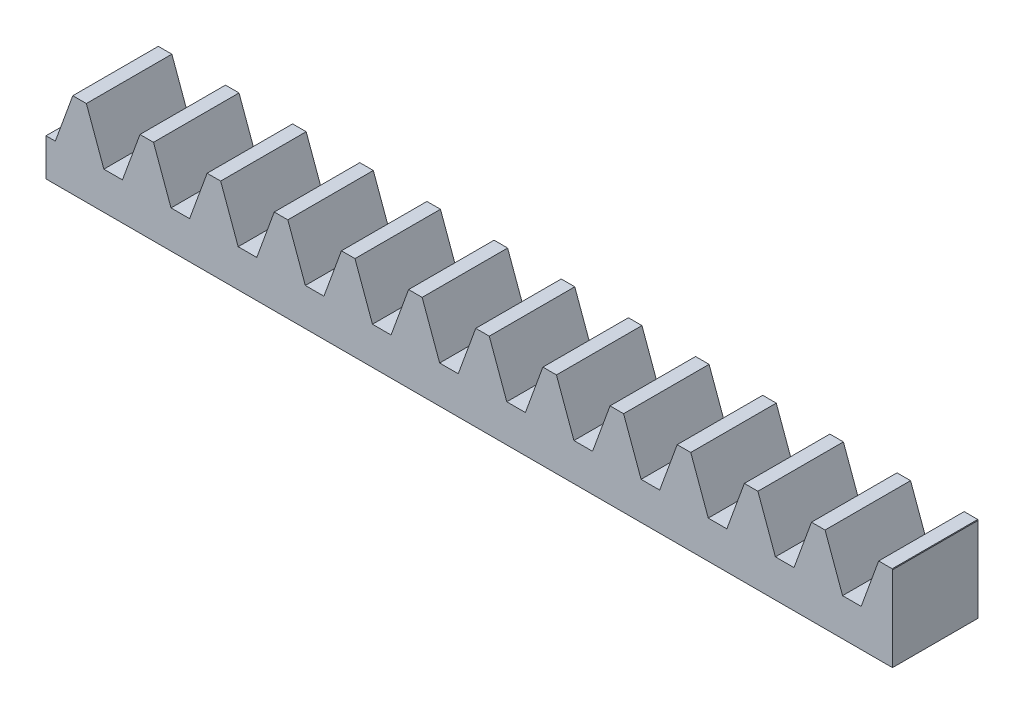
SolidWorks part; units mm, degrees
extrude "Blank" add sketch "BlankSke" against normal blind 10
sketch "BlankSke" plane through (0, 0, 0) normal (0, 0, 1) x (1, 0, 0)
  line L1 (0, 0) -> (99, 0)
  line L2 (0, 0) -> (0, 10)
  line L3 (0, 10) -> (99, 10)
  line L4 (99, 0) -> (99, 10)
  dimension "Length" = 99
  dimension "Blank_height" = 10
ref_plane "Plane1" through (0, 0, 0) normal (0, 0, 1) x (1, 0, 0)
ref_plane "Plane2" through (0, 0, 0) normal (0, 1, 0) x (1, 0, 0)
ref_plane "Plane3" through (0, 0, 0) normal (1, 0, 0) x (0, 0, -1)
sketch "HoldingSke" plane through (0, 0, 0) normal (0, 1, 0) x (1, 0, 0)
  line L0 (0, 0) -> (0.0557, 0.3961)
  line L1 (-15, 0) -> (100, 0) construction
  line L2 (0, 0) -> (-2.1039, 2.3779)
  line L3 (0, 0) -> (-11.863, 4.5341)
  line L4 (0, 0) -> (8.3795, 2.0892)
  line L5 (0, 0) -> (-23.7986, -8.8762)
  line L6 (0, 0) -> (-10.5278, -7.1032)
  line L9 (-71.009, 38.7566) -> (22.0206, 72.6166)
  line L10 (-76.2, 4.8779) -> (-68.7, 4.8779)
  line L11 (0, 0) -> (-10, 0)
  line L12 (-76.2, 101.6) -> (-76.113, 101.6)
  line L13 (24.9733, 27.94) -> (52.9518, 28.4284)
  line L14 (24.9733, 27.94) -> (24.9743, 27.94)
  line L15 (24.9733, 27.94) -> (100.4006, 29.5858)
  circle A0 centre (0, 0) radius 19.05
  circle A1 centre (0, 0) radius 3.75
  circle A2 centre (0, 0) radius 12.7
  dimension "MPH" = 7.5
  dimension "Diameter" = 38.1
  dimension "Num_teeth" = 14
  dimension "Pitch" = 0.4
  dimension "Show_teeth" = 998
  dimension "Thickness" = 12.7
  dimension "Ap" = 20
  dimension "Pitch_height" = 7.5
  dimension "Width" = 10
  dimension "Backlash" = 0.087
  dimension "Addendum_fac" = 1
  dimension "Dedendum_fac" = 1.25
  dimension "Clearance_fac" = 0.25
  dimension "Dedendum_add" = 0.001
  dimension "Length" = 99
  dimension "Module" = 2.5
sketch "TooCutSkeIll" plane through (0, 0, 0) normal (0, 0, 1) x (1, 0, 0)
  line L0 (-3.1105, 9.9342) -> (-1.237, 4.7869)
  line L1 (-0.6488, 4.375) -> (0.6488, 4.375)
  line L2 (1.237, 4.7869) -> (3.1105, 9.9342)
  line L3 (99, 10) -> (0, 10) construction
  line L4 (0, 0) -> (0, 64.897) construction
  line L5 (-13.208, 7.5) -> (12.954, 7.5) construction
  line L6 (0, 0) -> (99, 0) construction
  line L7 (2.2245, 7.5) -> (2.2245, 48.7463) construction
  line L8 (-2.2245, 7.5) -> (-2.2245, 48.7463) construction
  line L9 (3.2044, 10) -> (3.2044, 10.0254)
  line L10 (-3.2044, 10) -> (-3.2044, 10.0254)
  line L11 (-3.2044, 10.0254) -> (3.2044, 10.0254)
  arc A0 (0.6488, 4.375) -> (1.237, 4.7869) centre (0.6488, 5.001) ccw
  arc A1 (-1.237, 4.7869) -> (-0.6488, 4.375) centre (-0.6488, 5.001) ccw
  arc A2 (3.2044, 10) -> (3.1105, 9.9342) centre (3.2044, 9.9) ccw
  arc A3 (-3.1105, 9.9342) -> (-3.2044, 10) centre (-3.2044, 9.9) ccw
  dimension "Pitch_height" = 7.5
  dimension "Addendum_plus" = 2.5254
  dimension "Pressure_angle" = 20
  dimension "Gap_width" = 4.449
  dimension "Dedendum" = 3.125
extrude "ToothCutIll" [suppressed] cut sketch "TooCutSkeIll" against normal through all
sketch "TooCutSkeSim" plane through (0, 0, 0) normal (0, 0, 1) x (1, 0, 0)
  line L0 (1.0871, 4.375) -> (-1.0871, 4.375)
  line L1 (3.1437, 10.0254) -> (1.0871, 4.375)
  line L2 (0, 17.4625) -> (0, 53.467) construction
  line L3 (3.1437, 10.0254) -> (-3.1437, 10.0254)
  line L6 (-3.1437, 10.0254) -> (-1.0871, 4.375)
  line L9 (-2.2245, 7.5) -> (2.2245, 7.5) construction
  line L10 (0, 0) -> (99, 0) construction
  line L11 (2.2245, 7.5) -> (2.2245, 53.467) construction
  line L12 (-2.2245, 7.5) -> (-2.2245, 53.467) construction
  dimension "Pitch_height" = 7.5
  dimension "Addendum_plus" = 2.5254
  dimension "Pressure_angle" = 20
  dimension "Gap_width" = 4.449
  dimension "Dedendum" = 3.125
extrude "ToothCutSim" cut sketch "TooCutSkeSim" against normal through all
pattern_linear "TeethCuts" count 13 spacing 7.854 along (1, 0, 0) of "ToothCutIll", "ToothCutSim"
equation "' \"Module@HoldingSke\" = 6.35"
equation "' \"Num_teeth@HoldingSke\" = 12"
equation "' \"Ap@HoldingSke\" =  20"
equation "' \"Ap@HoldingSke\" = 20"
equation "' \"Width@HoldingSke\" = 0.25 * 25.4"
equation "' \"Show_teeth@HoldingSke\" = 500"
equation "' \"Backlash@HoldingSke\" = 0.009 * 25.4"
equation "' \"Addendum_fac@HoldingSke\" = 1.0"
equation "' \"Dedendum_fac@HoldingSke\" = 1.25"
equation "' \"Dedendum_add@HoldingSke\" = 0.00005 * 25.4"
equation "' \"Clearance_fac@HoldingSke\" = 0.25"
equation "' \"Pitch_height@HoldingSke\" = 1 * 25.4"
equation "' \"Length@HoldingSke\" = 4.71 * 25.4"
equation "\"Pitch@HoldingSke\" = 1 / \"Module@HoldingSke\""
equation "\"MPH@HoldingSke\" = \"Dedendum_fac@HoldingSke\" / \"Pitch@HoldingSke\" + 2 * \"Dedendum_add@HoldingSke\" + 0.002 * 25.4"
equation "\"MPH@HoldingSke\" = ((sgn( \"MPH@HoldingSke\" - \"Pitch_height@HoldingSke\")+1)*( \"MPH@HoldingSke\" - \"Pitch_height@HoldingSke\"))/2 + \"Pitch_height@HoldingSke\""
equation "\"Blank_height@BlankSke\" = \"Pitch_height@HoldingSke\" + \"Addendum_fac@HoldingSke\"  / \"Pitch@HoldingSke\" "
equation "\"Length@BlankSke\" =  \"Length@HoldingSke\""
equation "\"Face_width@Blank\" = \"Width@HoldingSke\""
equation "\"Pressure_angle@TooCutSkeIll\" = \"Ap@HoldingSke\""
equation "\"Addendum_plus@TooCutSkeIll\" =  \"Addendum_fac@HoldingSke\"  / \"Pitch@HoldingSke\" + 0.001 *25.4"
equation "\"Dedendum@TooCutSkeIll\" = \"Dedendum_fac@HoldingSke\"  / \"Pitch@HoldingSke\""
equation "\"Pitch_height@TooCutSkeIll\" =  \"MPH@HoldingSke\""
equation "\"Gap_width@TooCutSkeIll\" = 3.14159265 / 2 / \"Pitch@HoldingSke\" + 6 * \"Backlash@HoldingSke\""
equation "\"Pressure_angle@TooCutSkeSim\" = \"Ap@HoldingSke\""
equation "\"Addendum_plus@TooCutSkeSim\" =  \"Addendum_fac@HoldingSke\"  / \"Pitch@HoldingSke\" + 0.001 * 25.4"
equation "\"Dedendum@TooCutSkeSim\" = \"Dedendum_fac@HoldingSke\"  / \"Pitch@HoldingSke\""
equation "\"Pitch_height@TooCutSkeSim\" =  \"MPH@HoldingSke\""
equation "\"Gap_width@TooCutSkeSim\" = 3.14159265 / 2 / \"Pitch@HoldingSke\" + 6 * \"Backlash@HoldingSke\""
equation "\"Root_fillet@TooCutSkeIll\" = \"Clearance_fac@HoldingSke\" / \"Pitch@HoldingSke\" + \"Dedendum_add@HoldingSke\""
equation "\"Break_rad@TooCutSkeIll\" = 0.02 / \"Pitch@HoldingSke\" * 2"
equation "\"Linear_pitch@TeethCuts\" = 3.14159265 / \"Pitch@HoldingSke\""
equation "\"Num_teeth@HoldingSke\" = int( ( \"Length@HoldingSke\" + 0 ) / (3.14159265 / \"Pitch@HoldingSke\")) + 0.9999  + 1"
equation " \"Num_teeth@TeethCuts\" = int( \"Show_teeth@HoldingSke\" ) + 1"
equation " \"Num_teeth@TeethCuts\" = ((sgn( \"Num_teeth@TeethCuts\" - \"Num_teeth@HoldingSke\" )-1)*( \"Num_teeth@TeethCuts\" - \"Num_teeth@HoldingSke\" ))/-2+ \"Num_teeth@HoldingSke\""
equation " \"Num_teeth@TeethCuts\" = ((sgn( \"Num_teeth@TeethCuts\" - 2.0)+1)*( \"Num_teeth@TeethCuts\" - 2.0))/2 +2.0"
